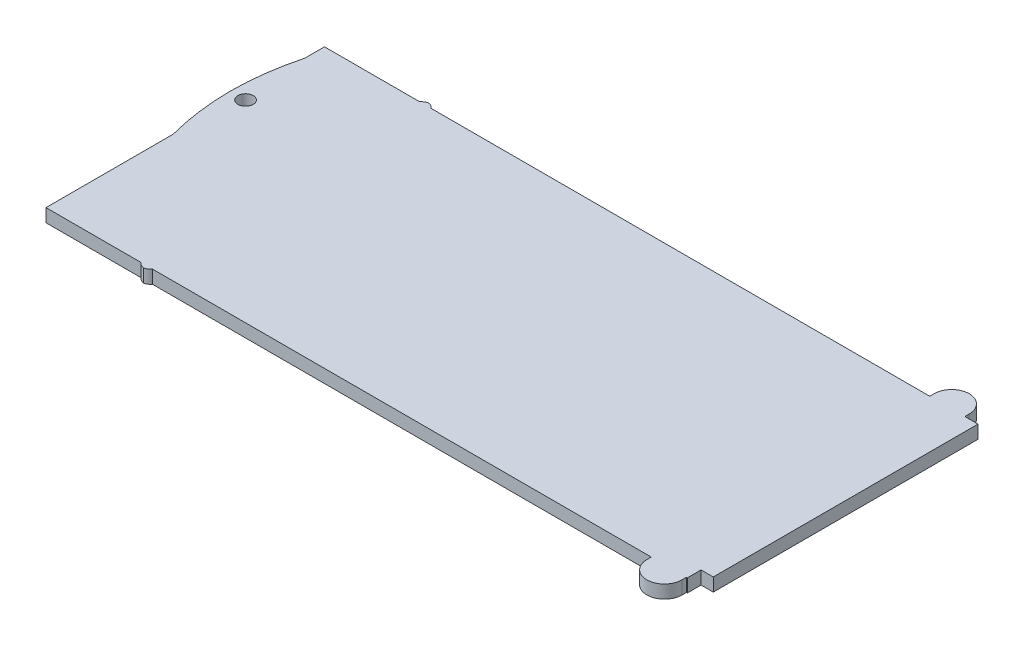
SolidWorks part; units mm, degrees
material "Vidrio"
ref_plane "Alzado" through (0, 0, 0) normal (0, 0, 1) x (1, 0, 0)
ref_plane "Planta" through (0, 0, 0) normal (0, 1, 0) x (1, 0, 0)
ref_plane "Vista lateral" through (0, 0, 0) normal (1, 0, 0) x (0, 0, -1)
sketch "Croquis1" plane through (0, 0, 0) normal (0, 1, 0) x (1, 0, 0)
  line L0 (32.5, -77.5) -> (54.1965, -77.5)
  line L1 (56.7974, -77.5) -> (170.5, -77.5)
  line L2 (170.5, -141) -> (56.7974, -141)
  line L3 (54.1965, -141) -> (32.5, -141)
  line L4 (32.5, -82) -> (32.5, -77.5)
  line L5 (32.5, -141) -> (32.5, -112)
  line L6 (178.7181, -141) -> (178.7181, -137.8604)
  line L7 (178.7181, -137.8604) -> (181.5, -137.8604)
  line L8 (181.5, -77.5) -> (181.5, -137.8604)
  line L9 (178.5, -77.5) -> (181.5, -77.5)
  line L10 (178.7181, -141) -> (178.5, -141)
  line L11 (170.5, -142) -> (170.5, -141)
  line L12 (178.5, -142) -> (178.5, -141)
  line L13 (170.5, -76.5) -> (170.5, -77.5)
  line L14 (178.5, -76.5) -> (178.5, -77.5)
  line L15 (99.7304, -88.3255) -> (86.8675, -88.4262) construction
  line L16 (86.8675, -88.4262) -> (90.5642, -101.9337) construction
  line L17 (96.8899, -125.7859) -> (94.6839, -125.655) construction
  line L18 (94.6839, -125.655) -> (89.4763, -106.6981) construction
  line L19 (127.2591, -94.0367) -> (128.6895, -98.0356) construction
  line L20 (128.6895, -98.0356) -> (122.8372, -101.0373) construction
  line L21 (110.065, -107.2521) -> (107.8288, -108.4508) construction
  line L22 (107.8288, -108.4508) -> (108.5944, -109.307) construction
  line L23 (113.8825, -115.0686) -> (118.2642, -119.8229) construction
  line L24 (118.2642, -119.8229) -> (120.0773, -125.242) construction
  line L25 (116.5619, -126.2803) -> (111.6766, -121.4144) construction
  line L26 (111.6766, -121.4144) -> (110.347, -122.2) construction
  line L27 (110.347, -122.2) -> (108.7052, -123.167) construction
  line L28 (108.7052, -123.167) -> (107.2648, -120.8503) construction
  line L29 (103.4673, -114.7059) -> (100.9592, -110.6365) construction
  line L30 (100.9592, -110.6365) -> (101.7147, -106.6578) construction
  line L31 (123.8344, -113.0338) -> (118.234, -116.9622) construction
  line L32 (118.234, -116.9622) -> (114.366, -113.1346) construction
  circle A0 centre (34, -97) radius 1.75 construction
  circle A1 centre (34, -97) radius 1.75
  arc A2 (56.7974, -77.5) -> (55.497, -76.7226) centre (55.1974, -78.7) ccw
  arc A3 (55.497, -76.7226) -> (54.1965, -77.5) centre (55.7965, -78.7) ccw
  arc A4 (54.1965, -141) -> (55.497, -141.7774) centre (55.7965, -139.8) ccw
  arc A5 (55.497, -141.7774) -> (56.7974, -141) centre (55.1974, -139.8) ccw
  arc A6 (32.5, -82) -> (30.5011, -97) centre (90.5, -97.3623) ccw
  arc A7 (30.5011, -97) -> (32.5, -112) centre (90.5, -96.6377) ccw
  arc A8 (170.5, -142) -> (178.5, -142) centre (174.5, -142) ccw
  arc A9 (178.5, -76.5) -> (170.5, -76.5) centre (174.5, -76.5) ccw
  spline S0 degree 3 poles (99.2469, -85.7972) (102.6549, -85.8219) (106.0847, -85.881) (108.7656, -85.9584) knots 0 0 0 0 1 1 1 1 construction
  spline S1 degree 3 poles (108.7656, -85.9584) (110.106, -85.997) (111.2548, -86.0394) (112.1299, -86.0893) knots 0 0 0 0 1 1 1 1 construction
  spline S2 degree 3 poles (112.1299, -86.0893) (113.0049, -86.1392) (113.5769, -86.1841) (113.8523, -86.2605) knots 0 0 0 0 1 1 1 1 construction
  spline S3 degree 3 poles (113.8523, -86.2605) (115.6771, -86.7671) (117.4794, -88.4676) (118.6872, -90.3501) knots 0 0 0 0 1 1 1 1 construction
  spline S4 degree 3 poles (118.6872, -90.3501) (119.2912, -91.2913) (119.7451, -92.279) (119.9665, -93.2007) knots 0 0 0 0 1 1 1 1 construction
  spline S5 degree 3 poles (119.9665, -93.2007) (120.1878, -94.1223) (120.1854, -94.9858) (119.8255, -95.6584) knots 0 0 0 0 1 1 1 1 construction
  spline S6 degree 3 poles (119.8255, -95.6584) (119.6598, -95.968) (119.5226, -96.1909) (119.342, -96.3333) knots 0 0 0 0 1 1 1 1 construction
  spline S7 degree 3 poles (119.342, -96.3333) (119.2517, -96.4045) (119.1346, -96.4558) (119.0096, -96.4441) knots 0 0 0 0 1 1 1 1 construction
  spline S8 degree 3 poles (119.0096, -96.4441) (118.8846, -96.4324) (118.772, -96.3609) (118.6872, -96.2728) knots 0 0 0 0 1 1 1 1 construction
  spline S9 degree 3 poles (118.6872, -96.2728) (118.5177, -96.0968) (118.3882, -95.8274) (118.2239, -95.4166) knots 0 0 0 0 1 1 1 1 construction
  spline S10 degree 3 poles (118.2239, -95.4166) (118.0596, -95.0059) (117.8762, -94.4609) (117.6497, -93.7547) knots 0 0 0 0 1 1 1 1 construction
  spline S11 degree 3 poles (117.6497, -93.7547) (116.7353, -90.9028) (115.8343, -89.6564) (114.1545, -88.8593) knots 0 0 0 0 1 1 1 1 construction
  spline S12 degree 3 poles (114.1545, -88.8593) (113.5775, -88.5856) (112.846, -88.4236) (110.8104, -88.3456) knots 0 0 0 0 1 1 1 1 construction
  spline S13 degree 3 poles (110.8104, -88.3456) (108.7748, -88.2676) (105.4596, -88.2788) (99.7304, -88.3255) knots 0 0 0 0 1 1 1 1 construction
  spline S14 degree 3 poles (90.5642, -101.9337) (92.6359, -109.5024) (94.8165, -117.4709) (95.4092, -119.6416) knots 0 0 0 0 1 1 1 1 construction
  spline S15 degree 3 poles (95.4092, -119.6416) (95.9453, -121.6053) (96.2253, -122.597) (96.4869, -123.0361) knots 0 0 0 0 1 1 1 1 construction
  spline S16 degree 3 poles (96.4869, -123.0361) (96.6178, -123.2556) (96.7202, -123.3315) (96.8697, -123.3785) knots 0 0 0 0 1 1 1 1 construction
  spline S17 degree 3 poles (96.8697, -123.3785) (97.0192, -123.4255) (97.2401, -123.4321) (97.5547, -123.4289) knots 0 0 0 0 1 1 1 1 construction
  spline S18 degree 3 poles (97.5547, -123.4289) (98.2, -123.4224) (99.1238, -123.1307) (99.4886, -122.8548) knots 0 0 0 0 1 1 1 1 construction
  spline S19 degree 3 poles (99.4886, -122.8548) (100.5827, -122.0273) (101.8952, -122.0605) (102.8731, -122.9454) knots 0 0 0 0 1 1 1 1 construction
  spline S20 degree 3 poles (102.8731, -122.9454) (103.7678, -123.7552) (103.8898, -124.9666) (103.2357, -126.1888) knots 0 0 0 0 1 1 1 1 construction
  spline S21 degree 3 poles (103.2357, -126.1888) (102.9216, -126.7757) (102.1414, -127.0425) (101.3521, -127.0853) knots 0 0 0 0 1 1 1 1 construction
  spline S22 degree 3 poles (101.3521, -127.0853) (100.5627, -127.1281) (99.735, -126.9479) (99.2972, -126.4205) knots 0 0 0 0 1 1 1 1 construction
  spline S23 degree 3 poles (99.2972, -126.4205) (99.2226, -126.3306) (98.8999, -126.1596) (98.4612, -126.0378) knots 0 0 0 0 1 1 1 1 construction
  spline S24 degree 3 poles (98.4612, -126.0378) (98.0225, -125.9159) (97.4641, -125.8197) (96.8899, -125.7859) knots 0 0 0 0 1 1 1 1 construction
  spline S25 degree 3 poles (89.4763, -106.6981) (88.0554, -101.522) (86.7608, -96.7432) (85.8199, -93.2107) knots 0 0 0 0 1 1 1 1 construction
  spline S26 degree 3 poles (85.8199, -93.2107) (85.3495, -91.4445) (84.9673, -89.9863) (84.7019, -88.95) knots 0 0 0 0 1 1 1 1 construction
  spline S27 degree 3 poles (84.7019, -88.95) (84.5691, -88.4318) (84.4607, -88.018) (84.3896, -87.7211) knots 0 0 0 0 1 1 1 1 construction
  spline S28 degree 3 poles (84.3896, -87.7211) (84.3541, -87.5727) (84.3281, -87.4583) (84.309, -87.3685) knots 0 0 0 0 1 1 1 1 construction
  spline S29 degree 3 poles (84.309, -87.3685) (84.2899, -87.2788) (84.2813, -87.2366) (84.2788, -87.1671) knots 0 0 0 0 1 1 1 1 construction
  spline S30 degree 3 poles (84.2788, -87.1671) (84.2622, -86.6938) (84.5775, -86.2305) (85.0242, -86.0591) knots 0 0 0 0 1 1 1 1 construction
  spline S31 degree 3 poles (85.0242, -86.0591) (85.1567, -86.0083) (85.3184, -85.9924) (85.5782, -85.9684) knots 0 0 0 0 1 1 1 1 construction
  spline S32 degree 3 poles (85.5782, -85.9684) (85.838, -85.9445) (86.1725, -85.9167) (86.5855, -85.8979) knots 0 0 0 0 1 1 1 1 construction
  spline S33 degree 3 poles (86.5855, -85.8979) (87.4114, -85.8603) (88.5315, -85.8368) (89.839, -85.8173) knots 0 0 0 0 1 1 1 1 construction
  spline S34 degree 3 poles (89.839, -85.8173) (92.4539, -85.7784) (95.8389, -85.7725) (99.2469, -85.7972) knots 0 0 0 0 1 1 1 1 construction
  spline S35 degree 3 poles (125.6072, -89.9472) (125.608, -89.9473) (125.7074, -89.997) (125.7079, -89.9975) knots 0 0 0 0 1 1 1 1 construction
  spline S36 degree 3 poles (125.7079, -89.9975) (125.709, -89.9986) (125.7327, -90.0201) (125.7381, -90.0278) knots 0 0 0 0 1 1 1 1 construction
  spline S37 degree 3 poles (125.7381, -90.0278) (125.7436, -90.0354) (125.7446, -90.042) (125.7482, -90.0479) knots 0 0 0 0 1 1 1 1 construction
  spline S38 degree 3 poles (125.7482, -90.0479) (125.7554, -90.0598) (125.7625, -90.0768) (125.7684, -90.0882) knots 0 0 0 0 1 1 1 1 construction
  spline S39 degree 3 poles (125.7684, -90.0882) (125.7801, -90.1111) (125.7946, -90.1372) (125.8086, -90.1688) knots 0 0 0 0 1 1 1 1 construction
  spline S40 degree 3 poles (125.8086, -90.1688) (125.8369, -90.2321) (125.8665, -90.3146) (125.9094, -90.4206) knots 0 0 0 0 1 1 1 1 construction
  spline S41 degree 3 poles (125.9094, -90.4206) (125.9951, -90.6327) (126.1156, -90.9272) (126.2519, -91.2869) knots 0 0 0 0 1 1 1 1 construction
  spline S42 degree 3 poles (126.2519, -91.2869) (126.5243, -92.0061) (126.8805, -92.9811) (127.2591, -94.0367) knots 0 0 0 0 1 1 1 1 construction
  spline S43 degree 3 poles (122.8372, -101.0373) (121.2681, -101.8388) (119.8053, -102.5696) (118.7175, -103.1022) knots 0 0 0 0 1 1 1 1 construction
  spline S44 degree 3 poles (118.7175, -103.1022) (118.1736, -103.3685) (117.7246, -103.5852) (117.3979, -103.7368) knots 0 0 0 0 1 1 1 1 construction
  spline S45 degree 3 poles (117.3979, -103.7368) (117.2346, -103.8125) (117.104, -103.8661) (117.0051, -103.908) knots 0 0 0 0 1 1 1 1 construction
  spline S46 degree 3 poles (117.0051, -103.908) (116.9556, -103.929) (116.9089, -103.9457) (116.8742, -103.9584) knots 0 0 0 0 1 1 1 1 construction
  spline S47 degree 3 poles (116.8742, -103.9584) (116.8568, -103.9647) (116.8402, -103.9738) (116.8238, -103.9786) knots 0 0 0 0 1 1 1 1 construction
  spline S48 degree 3 poles (116.8238, -103.9786) (116.8074, -103.9834) (116.7683, -103.9883) (116.7633, -103.9886) knots 0 0 0 0 1 1 1 1 construction
  spline S49 degree 3 poles (116.7633, -103.9886) (116.7621, -103.9887) (116.6938, -103.9788) (116.6928, -103.9786) knots 0 0 0 0 1 1 1 1 construction
  spline S50 degree 3 poles (116.6928, -103.9786) (116.6918, -103.9783) (116.613, -103.939) (116.6122, -103.9383) knots 0 0 0 0 1 1 1 1 construction
  spline S51 degree 3 poles (116.6122, -103.9383) (116.6115, -103.9376) (116.5624, -103.8688) (116.5618, -103.8678) knots 0 0 0 0 1 1 1 1 construction
  spline S52 degree 3 poles (116.5618, -103.8678) (116.5613, -103.8667) (116.5419, -103.8188) (116.5417, -103.8174) knots 0 0 0 0 1 1 1 1 construction
  spline S53 degree 3 poles (116.5417, -103.8174) (116.5414, -103.816) (116.5316, -103.7789) (116.5316, -103.7771) knots 0 0 0 0 1 1 1 1 construction
  spline S54 degree 3 poles (116.5316, -103.7771) (116.5316, -103.7753) (116.5408, -103.7553) (116.5417, -103.7469) knots 0 0 0 0 1 1 1 1 construction
  spline S55 degree 3 poles (116.5417, -103.7469) (116.5435, -103.73) (116.5387, -103.7188) (116.5417, -103.7066) knots 0 0 0 0 1 1 1 1 construction
  spline S56 degree 3 poles (116.5417, -103.7066) (116.5538, -103.6579) (116.5691, -103.6162) (116.5921, -103.5656) knots 0 0 0 0 1 1 1 1 construction
  spline S57 degree 3 poles (116.5921, -103.5656) (116.638, -103.4643) (116.7156, -103.3287) (116.8137, -103.1526) knots 0 0 0 0 1 1 1 1 construction
  spline S58 degree 3 poles (116.8137, -103.1526) (117.0098, -102.8003) (117.3084, -102.2959) (117.69, -101.6718) knots 0 0 0 0 1 1 1 1 construction
  spline S59 degree 3 poles (117.69, -101.6718) (118.4534, -100.4236) (119.5458, -98.7038) (120.7824, -96.8067) knots 0 0 0 0 1 1 1 1 construction
  spline S60 degree 3 poles (120.7824, -96.8067) (122.0188, -94.91) (123.1573, -93.2005) (123.9956, -91.9718) knots 0 0 0 0 1 1 1 1 construction
  spline S61 degree 3 poles (123.9956, -91.9718) (124.4147, -91.3574) (124.7576, -90.8595) (125.0028, -90.5213) knots 0 0 0 0 1 1 1 1 construction
  spline S62 degree 3 poles (125.0028, -90.5213) (125.1255, -90.3522) (125.2222, -90.2283) (125.295, -90.1386) knots 0 0 0 0 1 1 1 1 construction
  spline S63 degree 3 poles (125.295, -90.1386) (125.3313, -90.0937) (125.3558, -90.0574) (125.3856, -90.0278) knots 0 0 0 0 1 1 1 1 construction
  spline S64 degree 3 poles (125.3856, -90.0278) (125.4005, -90.0129) (125.4169, -89.9962) (125.446, -89.9774) knots 0 0 0 0 1 1 1 1 construction
  spline S65 degree 3 poles (125.446, -89.9774) (125.4533, -89.9727) (125.475, -89.9679) (125.4763, -89.9673) knots 0 0 0 0 1 1 1 1 construction
  spline S66 degree 3 poles (125.4763, -89.9673) (125.4775, -89.9667) (125.5155, -89.9474) (125.5165, -89.9472) knots 0 0 0 0 1 1 1 1 construction
  spline S67 degree 3 poles (125.5165, -89.9472) (125.5176, -89.9469) (125.6064, -89.947) (125.6072, -89.9472) knots 0 0 0 0 1 1 1 1 construction
  spline S68 degree 3 poles (92.8305, -92.3646) (92.9071, -92.3649) (92.9991, -92.3724) (93.1126, -92.3848) knots 0 0 0 0 1 1 1 1 construction
  spline S69 degree 3 poles (93.1126, -92.3848) (93.3396, -92.4096) (93.6479, -92.4503) (94.0191, -92.5157) knots 0 0 0 0 1 1 1 1 construction
  spline S70 degree 3 poles (94.0191, -92.5157) (94.7615, -92.6465) (95.7578, -92.8523) (96.8294, -93.0999) knots 0 0 0 0 1 1 1 1 construction
  spline S71 degree 3 poles (96.8294, -93.0999) (98.7138, -93.5354) (99.6932, -93.7597) (100.4455, -93.7849) knots 0 0 0 0 1 1 1 1 construction
  spline S72 degree 3 poles (100.4455, -93.7849) (101.1978, -93.8101) (101.7445, -93.6474) (102.8126, -93.3115) knots 0 0 0 0 1 1 1 1 construction
  spline S73 degree 3 poles (102.8126, -93.3115) (105.1556, -92.5745) (106.837, -92.6969) (108.9268, -93.7647) knots 0 0 0 0 1 1 1 1 construction
  spline S74 degree 3 poles (108.9268, -93.7647) (109.8304, -94.2265) (110.4968, -94.9706) (110.9514, -96.0915) knots 0 0 0 0 1 1 1 1 construction
  spline S75 degree 3 poles (110.9514, -96.0915) (111.4059, -97.2125) (111.6654, -98.7094) (111.8076, -100.7552) knots 0 0 0 0 1 1 1 1 construction
  spline S76 degree 3 poles (111.8076, -100.7552) (111.8769, -101.7533) (111.9712, -102.7384) (112.0694, -103.5151) knots 0 0 0 0 1 1 1 1 construction
  spline S77 degree 3 poles (112.0694, -103.5151) (112.1185, -103.9035) (112.1637, -104.2427) (112.2105, -104.5023) knots 0 0 0 0 1 1 1 1 construction
  spline S78 degree 3 poles (112.2105, -104.5023) (112.2573, -104.7619) (112.3097, -104.9563) (112.3313, -105.0059) knots 0 0 0 0 1 1 1 1 construction
  spline S79 degree 3 poles (112.3313, -105.0059) (112.4028, -105.1697) (112.4299, -105.3513) (112.3716, -105.5297) knots 0 0 0 0 1 1 1 1 construction
  spline S80 degree 3 poles (112.3716, -105.5297) (112.3133, -105.7081) (112.1899, -105.8684) (112.009, -106.0333) knots 0 0 0 0 1 1 1 1 construction
  spline S81 degree 3 poles (112.009, -106.0333) (111.6473, -106.3631) (111.0357, -106.7347) (110.065, -107.2521) knots 0 0 0 0 1 1 1 1 construction
  spline S82 degree 3 poles (108.5944, -109.307) (109.112, -109.8803) (111.4929, -112.4731) (113.8825, -115.0686) knots 0 0 0 0 1 1 1 1 construction
  spline S83 degree 3 poles (120.0773, -125.242) (120.5739, -126.7228) (121.029, -128.0947) (121.3565, -129.1099) knots 0 0 0 0 1 1 1 1 construction
  spline S84 degree 3 poles (121.3565, -129.1099) (121.5203, -129.6176) (121.6471, -130.0383) (121.7393, -130.3388) knots 0 0 0 0 1 1 1 1 construction
  spline S85 degree 3 poles (121.7393, -130.3388) (121.7854, -130.489) (121.8251, -130.6027) (121.8501, -130.6914) knots 0 0 0 0 1 1 1 1 construction
  spline S86 degree 3 poles (121.8501, -130.6914) (121.8625, -130.7357) (121.8731, -130.7724) (121.8803, -130.8021) knots 0 0 0 0 1 1 1 1 construction
  spline S87 degree 3 poles (121.8803, -130.8021) (121.8839, -130.8171) (121.8878, -130.8388) (121.8903, -130.8527) knots 0 0 0 0 1 1 1 1 construction
  spline S88 degree 3 poles (121.8903, -130.8527) (121.8929, -130.8661) (121.8903, -130.8996) (121.8903, -130.9032) knots 0 0 0 0 1 1 1 1 construction
  spline S89 degree 3 poles (121.8903, -130.9032) (121.8903, -130.9041) (121.8805, -130.9832) (121.8803, -130.9838) knots 0 0 0 0 1 1 1 1 construction
  spline S90 degree 3 poles (121.4673, -131.0045) (121.3936, -130.9463) (121.2933, -130.8577) (121.1651, -130.7426) knots 0 0 0 0 1 1 1 1 construction
  spline S91 degree 3 poles (121.1651, -130.7426) (120.9086, -130.5125) (120.5405, -130.168) (120.0873, -129.7353) knots 0 0 0 0 1 1 1 1 construction
  spline S92 degree 3 poles (120.0873, -129.7353) (119.1811, -128.8699) (117.9352, -127.6503) (116.5619, -126.2803) knots 0 0 0 0 1 1 1 1 construction
  spline S93 degree 3 poles (107.2648, -120.8503) (106.5327, -119.668) (104.824, -116.9043) (103.4673, -114.7059) knots 0 0 0 0 1 1 1 1 construction
  spline S94 degree 3 poles (101.7147, -106.6578) (102.1211, -104.517) (102.5727, -101.6631) (102.7119, -100.3422) knots 0 0 0 0 1 1 1 1 construction
  spline S95 degree 3 poles (102.7119, -100.3422) (102.8306, -99.2158) (102.8703, -98.6044) (102.7723, -98.1866) knots 0 0 0 0 1 1 1 1 construction
  spline S96 degree 3 poles (102.7723, -98.1866) (102.6744, -97.7689) (102.4426, -97.5035) (101.9464, -97.0081) knots 0 0 0 0 1 1 1 1 construction
  spline S97 degree 3 poles (101.9464, -97.0081) (101.6593, -96.7216) (100.9809, -96.2962) (100.0628, -95.8498) knots 0 0 0 0 1 1 1 1 construction
  spline S98 degree 3 poles (100.0628, -95.8498) (99.1446, -95.4033) (97.9882, -94.9257) (96.7086, -94.4698) knots 0 0 0 0 1 1 1 1 construction
  spline S99 degree 3 poles (96.7086, -94.4698) (95.5391, -94.0532) (94.4984, -93.6507) (93.7572, -93.3417) knots 0 0 0 0 1 1 1 1 construction
  spline S100 degree 3 poles (93.7572, -93.3417) (93.3866, -93.1872) (93.0835, -93.0618) (92.8809, -92.9589) knots 0 0 0 0 1 1 1 1 construction
  spline S101 degree 3 poles (92.8809, -92.9589) (92.7796, -92.9074) (92.7109, -92.8618) (92.6492, -92.8179) knots 0 0 0 0 1 1 1 1 construction
  spline S102 degree 3 poles (92.6492, -92.8179) (92.6184, -92.796) (92.5916, -92.7813) (92.5586, -92.7373) knots 0 0 0 0 1 1 1 1 construction
  spline S103 degree 3 poles (92.5586, -92.7373) (92.5503, -92.7263) (92.5296, -92.6894) (92.5284, -92.6869) knots 0 0 0 0 1 1 1 1 construction
  spline S104 degree 3 poles (92.5284, -92.6869) (92.5272, -92.6844) (92.5085, -92.6287) (92.5082, -92.6265) knots 0 0 0 0 1 1 1 1 construction
  spline S105 degree 3 poles (92.5082, -92.6265) (92.5079, -92.6243) (92.5176, -92.5276) (92.5183, -92.5258) knots 0 0 0 0 1 1 1 1 construction
  spline S106 degree 3 poles (92.5183, -92.5258) (92.5189, -92.5239) (92.5671, -92.4468) (92.5686, -92.4452) knots 0 0 0 0 1 1 1 1 construction
  spline S107 degree 3 poles (92.5686, -92.4452) (92.5702, -92.4436) (92.6166, -92.4063) (92.619, -92.4049) knots 0 0 0 0 1 1 1 1 construction
  spline S108 degree 3 poles (92.619, -92.4049) (92.6214, -92.4036) (92.6474, -92.389) (92.6593, -92.3848) knots 0 0 0 0 1 1 1 1 construction
  spline S109 degree 3 poles (92.6593, -92.3848) (92.6831, -92.3763) (92.7014, -92.3775) (92.7197, -92.3747) knots 0 0 0 0 1 1 1 1 construction
  spline S110 degree 3 poles (92.7197, -92.3747) (92.7565, -92.369) (92.7923, -92.3645) (92.8305, -92.3646) knots 0 0 0 0 1 1 1 1 construction
  spline S111 degree 3 poles (133.6956, -97.6628) (133.6978, -97.663) (133.7545, -97.6724) (133.756, -97.6729) knots 0 0 0 0 1 1 1 1 construction
  spline S112 degree 3 poles (133.756, -97.6729) (133.7575, -97.6734) (133.8358, -97.7225) (133.8366, -97.7233) knots 0 0 0 0 1 1 1 1 construction
  spline S113 degree 3 poles (133.8366, -97.7233) (133.839, -97.7257) (133.875, -97.7802) (133.8769, -97.7837) knots 0 0 0 0 1 1 1 1 construction
  spline S114 degree 3 poles (133.8769, -97.7837) (133.8788, -97.7872) (133.8924, -97.8093) (133.8971, -97.824) knots 0 0 0 0 1 1 1 1 construction
  spline S115 degree 3 poles (133.8971, -97.824) (133.9064, -97.8535) (133.9152, -97.8807) (133.9172, -97.9046) knots 0 0 0 0 1 1 1 1 construction
  spline S116 degree 3 poles (133.9172, -97.9046) (133.9213, -97.9524) (133.9124, -97.9948) (133.9072, -98.0456) knots 0 0 0 0 1 1 1 1 construction
  spline S117 degree 3 poles (133.9072, -98.0456) (133.8966, -98.1473) (133.8814, -98.2787) (133.8467, -98.4284) knots 0 0 0 0 1 1 1 1 construction
  spline S118 degree 3 poles (133.8467, -98.4284) (133.7773, -98.7277) (133.662, -99.1221) (133.5143, -99.5968) knots 0 0 0 0 1 1 1 1 construction
  spline S119 degree 3 poles (133.5143, -99.5968) (133.2189, -100.5461) (132.7837, -101.7908) (132.3258, -103.0417) knots 0 0 0 0 1 1 1 1 construction
  spline S120 degree 3 poles (132.3258, -103.0417) (131.8678, -104.2926) (131.3819, -105.5533) (130.9659, -106.547) knots 0 0 0 0 1 1 1 1 construction
  spline S121 degree 3 poles (130.9659, -106.547) (130.758, -107.0438) (130.5723, -107.4762) (130.4119, -107.8061) knots 0 0 0 0 1 1 1 1 construction
  spline S122 degree 3 poles (130.4119, -107.8061) (130.2515, -108.136) (130.1447, -108.3438) (130.009, -108.481) knots 0 0 0 0 1 1 1 1 construction
  spline S123 degree 3 poles (130.009, -108.481) (129.8916, -108.5997) (129.6547, -108.7967) (129.2939, -109.0752) knots 0 0 0 0 1 1 1 1 construction
  spline S124 degree 3 poles (129.2939, -109.0752) (128.933, -109.3537) (128.4515, -109.7023) (127.8938, -110.1127) knots 0 0 0 0 1 1 1 1 construction
  spline S125 degree 3 poles (127.8938, -110.1127) (126.7783, -110.9336) (125.3382, -111.9786) (123.8344, -113.0338) knots 0 0 0 0 1 1 1 1 construction
  spline S126 degree 3 poles (114.366, -113.1346) (113.3352, -112.1144) (112.3977, -111.1632) (111.7169, -110.4452) knots 0 0 0 0 1 1 1 1 construction
  spline S127 degree 3 poles (111.7169, -110.4452) (111.3765, -110.0861) (111.1044, -109.7898) (110.9111, -109.5688) knots 0 0 0 0 1 1 1 1 construction
  spline S128 degree 3 poles (110.9111, -109.5688) (110.8144, -109.4583) (110.7344, -109.3686) (110.6794, -109.2969) knots 0 0 0 0 1 1 1 1 construction
  spline S129 degree 3 poles (110.6794, -109.2969) (110.6519, -109.261) (110.628, -109.2271) (110.6089, -109.1961) knots 0 0 0 0 1 1 1 1 construction
  spline S130 degree 3 poles (110.6089, -109.1961) (110.5994, -109.1807) (110.5977, -109.166) (110.5887, -109.1458) knots 0 0 0 0 1 1 1 1 construction
  spline S131 degree 3 poles (110.5887, -109.1458) (110.5843, -109.1356) (110.5694, -109.1084) (110.5686, -109.1055) knots 0 0 0 0 1 1 1 1 construction
  spline S132 degree 3 poles (110.5686, -109.1055) (110.5678, -109.1026) (110.5585, -109.0471) (110.5585, -109.045) knots 0 0 0 0 1 1 1 1 construction
  spline S133 degree 3 poles (110.5585, -109.045) (110.5585, -109.0438) (110.578, -108.9559) (110.5787, -108.9544) knots 0 0 0 0 1 1 1 1 construction
  spline S134 degree 3 poles (110.5787, -108.9544) (110.5794, -108.9529) (110.6075, -108.916) (110.6089, -108.9141) knots 0 0 0 0 1 1 1 1 construction
  spline S135 degree 3 poles (110.6089, -108.9141) (110.6117, -108.9104) (110.6379, -108.8841) (110.6492, -108.8738) knots 0 0 0 0 1 1 1 1 construction
  spline S136 degree 3 poles (110.6492, -108.8738) (110.6718, -108.8532) (110.6841, -108.8412) (110.7096, -108.8234) knots 0 0 0 0 1 1 1 1 construction
  spline S137 degree 3 poles (110.7096, -108.8234) (110.7607, -108.7879) (110.8356, -108.7428) (110.9212, -108.6925) knots 0 0 0 0 1 1 1 1 construction
  spline S138 degree 3 poles (110.9212, -108.6925) (111.0923, -108.5919) (111.3342, -108.4561) (111.6464, -108.2896) knots 0 0 0 0 1 1 1 1 construction
  spline S139 degree 3 poles (111.6464, -108.2896) (112.2707, -107.9565) (113.1574, -107.4994) (114.225, -106.96) knots 0 0 0 0 1 1 1 1 construction
  spline S140 degree 3 poles (114.225, -106.96) (116.3602, -105.8811) (119.2074, -104.4731) (122.0616, -103.082) knots 0 0 0 0 1 1 1 1 construction
  spline S141 degree 3 poles (122.0616, -103.082) (124.9158, -101.6909) (127.7776, -100.3197) (129.9385, -99.3047) knots 0 0 0 0 1 1 1 1 construction
  spline S142 degree 3 poles (129.9385, -99.3047) (131.0189, -98.7972) (131.9237, -98.381) (132.5675, -98.096) knots 0 0 0 0 1 1 1 1 construction
  spline S143 degree 3 poles (132.5675, -98.096) (132.8893, -97.9535) (133.1501, -97.8355) (133.333, -97.7636) knots 0 0 0 0 1 1 1 1 construction
  spline S144 degree 3 poles (133.333, -97.7636) (133.4244, -97.7276) (133.4958, -97.7009) (133.5546, -97.683) knots 0 0 0 0 1 1 1 1 construction
  spline S145 degree 3 poles (133.5546, -97.683) (133.584, -97.674) (133.6042, -97.6677) (133.6352, -97.6628) knots 0 0 0 0 1 1 1 1 construction
  spline S146 degree 3 poles (133.6352, -97.6628) (133.6506, -97.6604) (133.6913, -97.6626) (133.6956, -97.6628) knots 0 0 0 0 1 1 1 1 construction
  spline S147 degree 3 poles (126.141, -113.3159) (126.1436, -113.3159) (126.2186, -113.3348) (126.2216, -113.336) knots 0 0 0 0 1 1 1 1 construction
  spline S148 degree 3 poles (126.2216, -113.336) (126.2246, -113.3373) (126.2588, -113.3569) (126.272, -113.3663) knots 0 0 0 0 1 1 1 1 construction
  spline S149 degree 3 poles (126.272, -113.3663) (126.2984, -113.3849) (126.3174, -113.3995) (126.3324, -113.4167) knots 0 0 0 0 1 1 1 1 construction
  spline S150 degree 3 poles (126.3324, -113.4167) (126.3626, -113.4509) (126.3868, -113.4846) (126.413, -113.5274) knots 0 0 0 0 1 1 1 1 construction
  spline S151 degree 3 poles (126.413, -113.5274) (126.4655, -113.6131) (126.5253, -113.7252) (126.5943, -113.8699) knots 0 0 0 0 1 1 1 1 construction
  spline S152 degree 3 poles (126.5943, -113.8699) (126.7323, -114.1594) (126.9039, -114.5721) (127.108, -115.0786) knots 0 0 0 0 1 1 1 1 construction
  spline S153 degree 3 poles (127.108, -115.0786) (127.5164, -116.0917) (128.044, -117.4841) (128.5786, -119.017) knots 0 0 0 0 1 1 1 1 construction
  spline S154 degree 3 poles (128.5786, -119.017) (129.6461, -122.0779) (130.5973, -124.8181) (130.6939, -125.0909) knots 0 0 0 0 1 1 1 1 construction
  spline S155 degree 3 poles (130.6939, -125.0909) (130.734, -125.204) (130.7463, -125.3306) (130.704, -125.4434) knots 0 0 0 0 1 1 1 1 construction
  spline S156 degree 3 poles (130.704, -125.4434) (130.6616, -125.5563) (130.5728, -125.6449) (130.4723, -125.7053) knots 0 0 0 0 1 1 1 1 construction
  spline S157 degree 3 poles (130.4723, -125.7053) (130.2714, -125.8263) (130.007, -125.8665) (129.6665, -125.8665) knots 0 0 0 0 1 1 1 1 construction
  spline S158 degree 3 poles (129.6665, -125.8665) (129.4156, -125.8665) (129.1747, -125.8401) (128.9513, -125.6953) knots 0 0 0 0 1 1 1 1 construction
  spline S159 degree 3 poles (128.9513, -125.6953) (128.728, -125.5504) (128.5364, -125.3043) (128.3369, -124.9197) knots 0 0 0 0 1 1 1 1 construction
  spline S160 degree 3 poles (128.3369, -124.9197) (127.9379, -124.1504) (127.466, -122.7731) (126.6044, -120.1956) knots 0 0 0 0 1 1 1 1 construction
  spline S161 degree 3 poles (126.6044, -120.1956) (125.9084, -118.1132) (125.4666, -116.6946) (125.2446, -115.7333) knots 0 0 0 0 1 1 1 1 construction
  spline S162 degree 3 poles (125.2446, -115.7333) (125.1335, -115.2527) (125.081, -114.8918) (125.0733, -114.6052) knots 0 0 0 0 1 1 1 1 construction
  spline S163 degree 3 poles (125.0733, -114.6052) (125.0656, -114.3186) (125.1001, -114.0922) (125.2345, -113.9303) knots 0 0 0 0 1 1 1 1 construction
  spline S164 degree 3 poles (125.2345, -113.9303) (125.3691, -113.7681) (125.526, -113.6264) (125.6777, -113.5173) knots 0 0 0 0 1 1 1 1 construction
  spline S165 degree 3 poles (125.6777, -113.5173) (125.8294, -113.4083) (125.9596, -113.3159) (126.141, -113.3159) knots 0 0 0 0 1 1 1 1 construction
  dimension "D1" = 60.3604
extrude "Saliente-Extruir1" add sketch "Croquis1" along normal blind 3
sketch "Croquis2" plane through (0, 0, 77.5) normal (0, 0, -1) x (-1, 0, 0)
  line L0 (-174.5, 0) -> (-174.5, 3) construction
  line L1 (-178.5, 0) -> (-170.5, 0) construction
  line L2 (-170.5, 3) -> (-178.5, 3) construction
  circle A0 centre (-174.5, 1.5) radius 5.2742 construction
